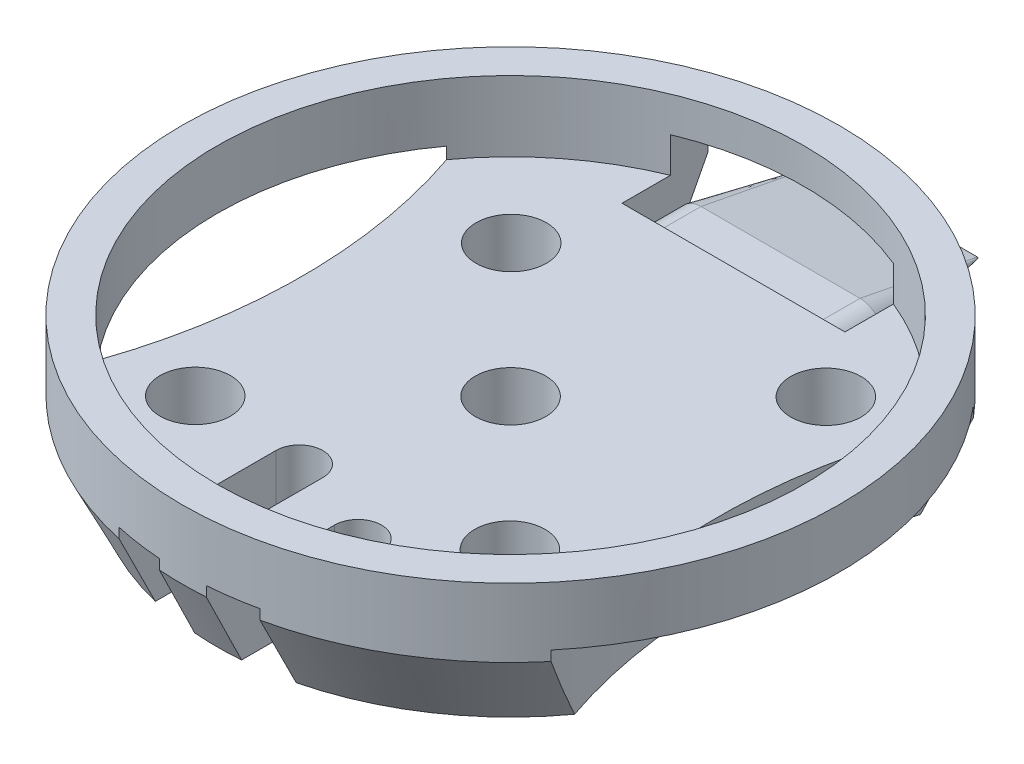
SolidWorks part; units mm, degrees
material "Acciaio al carbonio semplice"
ref_plane "Piano frontale" through (0, 0, 0) normal (0, 0, 1) x (1, 0, 0)
ref_plane "Piano superiore" through (0, 0, 0) normal (0, 1, 0) x (1, 0, 0)
ref_plane "Piano destro" through (0, 0, 0) normal (1, 0, 0) x (0, 0, -1)
sketch "Schizzo1" plane through (0, 0, 0) normal (0, 1, 0) x (1, 0, 0)
  circle A0 centre (0, 0) radius 14
extrude "Estrusione-Estrusione1" add sketch "Schizzo1" along normal blind 6
sketch "Schizzo2" plane through (0, 0, 0) normal (0, -1, 0) x (1, 0, 0)
  line L1 (4.75, -9.5) -> (-4.75, -9.5)
  line L2 (4.75, -9.5) -> (4.75, -14.5)
  line L3 (4.75, -14.5) -> (-4.75, -14.5)
  line L4 (-4.75, -9.5) -> (-4.75, -14.5)
  circle A0 centre (0, 0) radius 4 construction
  circle A1 centre (0, 0) radius 14 construction
  point P7 (0, -9.5)
  point P10 (0, -14)
  dimension "D1" = 9.5
  dimension "D2" = 4.5
  dimension "D3" = 5
extrude "Taglio-Estrusione1" cut sketch "Schizzo2" against normal blind 4.5
sketch "Schizzo3" plane through (0, 6, 0) normal (0, 1, 0) x (1, 0, 0)
  circle A0 centre (0, 0) radius 12.5
  circle A1 centre (0, 0) radius 14 construction
  dimension "D1" = 1.5
extrude "Taglio-Estrusione2" cut sketch "Schizzo3" against normal blind 3
sketch "Schizzo4" plane through (0, 0, 0) normal (0, -1, 0) x (1, 0, 0)
  line L0 (0, 0) -> (0, 14.7714) construction
  line L1 (-1, 14.7714) -> (-1, 6.8632)
  line L2 (1, 14.7714) -> (1, 8.5)
  line L3 (-3, 7) -> (-3, 14.7714)
  line L4 (3, 14.7714) -> (3, 8.5)
  line L5 (-3, 14.7714) -> (-1, 14.7714)
  line L6 (1, 14.7714) -> (3, 14.7714)
  arc A0 (-3, 7) -> (-1, 7) centre (-2, 7) ccw
  arc A1 (1, 8.5) -> (3, 8.5) centre (2, 8.5) ccw
  arc A2 (4.75, -13.1696) -> (-4.75, -13.1696) centre (0, 0) ccw construction
  point P15 (-2, 6)
  point P16 (0, 14)
  point P17 (2, 7.5)
  arc M4 (4.75, -13.1696) -> (-4.75, -13.1696) centre (0, 0) ccw
  dimension "D5" = 8
  dimension "D1" = 1
  dimension "D2" = 1
  dimension "D3" = 2
  dimension "D4" = 2
  dimension "D6" = 6.5
extrude "Taglio-Estrusione4" cut sketch "Schizzo4" against normal blind 3.5 contours L3 A0 L1 M4 | L2 A1 L4 M4
chamfer "Smusso1" distance 1.5 angle 64 3 edges at (13.9703, 0, 0.9107) (-13.9703, 0, 0.9107) (0, 0, 14)
sketch "Schizzo8" plane through (0, 0, 0) normal (0, -1, 0) x (1, 0, 0)
  line L0 (0, 15.0538) -> (0, -7.654) construction
  line L1 (-10.7238, -9) -> (-10.7238, 9) construction
  circle A0 centre (-31.649, 0) radius 22.7786
  circle A2 centre (31.649, 0) radius 22.7786
  arc A3 (-3, 13.6748) -> (-4.75, -13.1696) centre (0, 0) ccw construction
  dimension "D1" = 18
extrude "Taglio-Estrusione6" cut sketch "Schizzo8" against normal blind 3.5
sketch "Schizzo10" plane through (0, 0, -9.5) normal (0, 0, -1) x (-1, 0, 0)
  line L0 (-3.3892, 2.5596) -> (3.3892, 2.5596)
  line L1 (3.3892, 0.5596) -> (-3.3892, 0.5596)
  arc A0 (-3.3892, 2.5596) -> (-3.3892, 0.5596) centre (-3.3892, 1.5596) ccw
  arc A1 (3.3892, 0.5596) -> (3.3892, 2.5596) centre (3.3892, 1.5596) ccw
extrude "Estrusione-Estrusione2" add sketch "Schizzo10" along normal blind 7
chamfer "Smusso2" distance 5 angle 11 4 edges at (4.3892, 1.5596, -16.5) (0, 0.5596, -16.5) (0, 2.5596, -16.5) (-4.3892, 1.5596, -16.5)
sketch "Schizzo14" plane through (0, 0, 0) normal (0, -1, 0) x (1, 0, 0)
  line L0 (-11.9633, -12.0218) -> (12.4003, 12.4609) construction
  line L1 (-12.2157, 12.1562) -> (13.9192, -13.8515) construction
  circle A0 centre (6.7339, -6.7011) radius 1.5
  circle A1 centre (-6.7339, 6.7011) radius 1.5
  circle A2 centre (5.643, 5.6706) radius 1.5
  circle A3 centre (-5.643, -5.6706) radius 1.5
  dimension "D2" = 8
  dimension "D1" = 90
  dimension "D3" = 8
  dimension "D4" = 9.5
  dimension "D5" = 9.5
extrude "Taglio-Estrusione10" cut sketch "Schizzo14" against normal through all
sketch "Schizzo17" plane through (0, 0, 0) normal (0, -1, 0) x (1, 0, 0)
  circle A0 centre (0, 0) radius 1.5
extrude "Taglio-Estrusione12" cut sketch "Schizzo17" against normal blind 32
